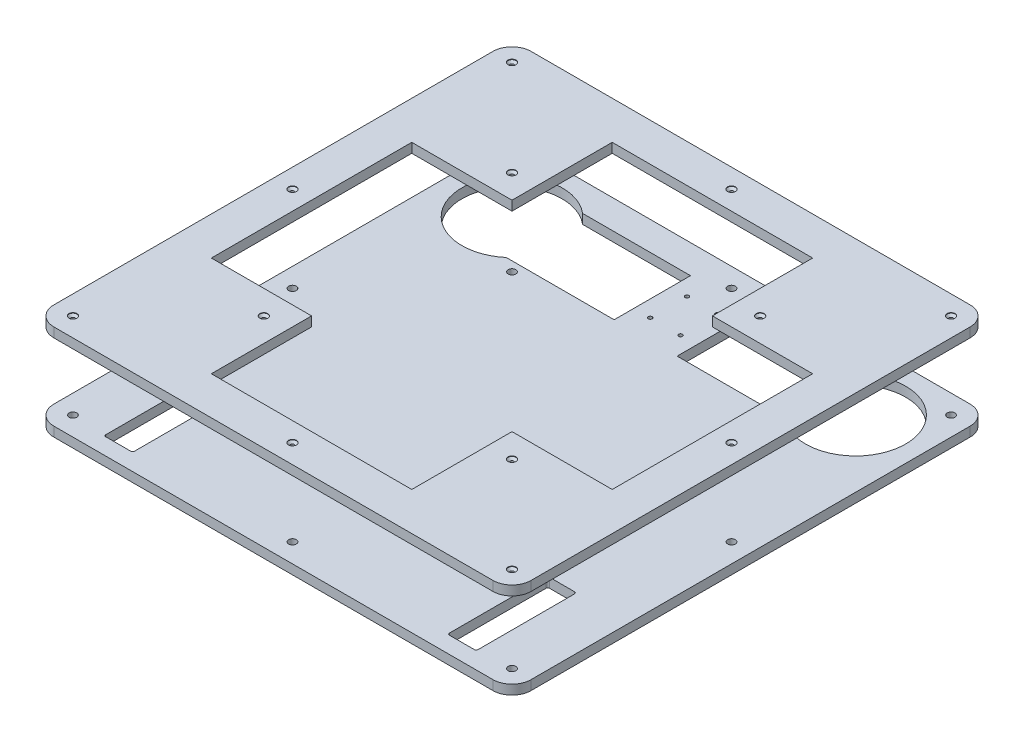
SolidWorks part; units mm, degrees
ref_plane "Front Plane" through (0, 0, 0) normal (0, 0, 1) x (1, 0, 0)
ref_plane "Top Plane" through (0, 0, 0) normal (0, 1, 0) x (1, 0, 0)
ref_plane "Right Plane" through (0, 0, 0) normal (1, 0, 0) x (0, 0, -1)
sketch "Sketch1" plane through (0, 0, 0) normal (0, 1, 0) x (1, 0, 0)
  line L0 (180, 180) -> (-180, 180) construction
  line L1 (-230, -250) -> (230, -250)
  line L2 (-250, -230) -> (-250, 230)
  line L3 (-230, 250) -> (230, 250)
  line L4 (250, -230) -> (250, 230)
  line L5 (-250, -250) -> (250, 250) construction
  line L6 (-250, 250) -> (250, -250) construction
  line L7 (0, 250) -> (0, -250) construction
  line L8 (-250, 0) -> (250, 0) construction
  line L9 (-193, -232.5) -> (-167, -232.5)
  line L10 (-195, -230.5) -> (-195, -129.5)
  line L11 (-193, -127.5) -> (-167, -127.5)
  line L12 (-165, -230.5) -> (-165, -129.5)
  line L13 (-195, -232.5) -> (-165, -127.5) construction
  line L14 (-195, -127.5) -> (-165, -232.5) construction
  line L15 (193, -232.5) -> (167, -232.5)
  line L16 (195, -230.5) -> (195, -129.5)
  line L17 (193, -127.5) -> (167, -127.5)
  line L18 (165, -230.5) -> (165, -129.5)
  line L19 (195, -232.5) -> (165, -127.5) construction
  line L20 (195, -127.5) -> (165, -232.5) construction
  line L21 (33, 220) -> (145.9963, 220)
  line L23 (33, 220) -> (33, 140)
  line L25 (-33, 220) -> (-33, 140)
  line L26 (33, 220) -> (-33, 140) construction
  line L27 (33, 140) -> (-33, 220) construction
  line L28 (33, 140) -> (145.9963, 140)
  line L29 (-33, 220) -> (-145.9963, 220)
  line L30 (-33, 140) -> (-145.9963, 140)
  arc A0 (230, 250) -> (250, 230) centre (230, 230) cw
  arc A1 (250, -230) -> (230, -250) centre (230, -230) cw
  arc A2 (-230, -250) -> (-250, -230) centre (-230, -230) cw
  arc A3 (-250, 230) -> (-230, 250) centre (-230, 230) cw
  circle A4 centre (-230, 230) radius 4
  circle A5 centre (230, 230) radius 4
  circle A6 centre (230, -230) radius 4
  circle A7 centre (-230, -230) radius 4
  arc A8 (-145.9963, 220) -> (-145.9963, 140) centre (-180, 180) ccw
  arc A9 (145.9963, 140) -> (145.9963, 220) centre (180, 180) ccw
  arc A10 (165, -230.5) -> (167, -232.5) centre (167, -230.5) ccw
  arc A11 (193, -232.5) -> (195, -230.5) centre (193, -230.5) ccw
  arc A12 (195, -129.5) -> (193, -127.5) centre (193, -129.5) ccw
  arc A13 (165, -129.5) -> (167, -127.5) centre (167, -129.5) cw
  arc A14 (-167, -127.5) -> (-165, -129.5) centre (-167, -129.5) cw
  arc A15 (-165, -230.5) -> (-167, -232.5) centre (-167, -230.5) cw
  arc A16 (-193, -232.5) -> (-195, -230.5) centre (-193, -230.5) cw
  arc A17 (-195, -129.5) -> (-193, -127.5) centre (-193, -129.5) cw
  circle A18 centre (0, 230) radius 4
  circle A19 centre (-230, 0) radius 4
  circle A20 centre (230, 0) radius 4
  circle A21 centre (0, -230) radius 4
  circle A22 centre (-130, 130) radius 4
  circle A23 centre (130, 130) radius 4
  circle A24 centre (-130, -130) radius 4
  circle A25 centre (130, -130) radius 4
  circle A27 centre (15.9096, 199.2843) radius 2
  circle A28 centre (15.9096, 160.7157) radius 2
  circle A29 centre (-15.9096, 160.7157) radius 2
  circle A30 centre (-15.9096, 199.2843) radius 2
  point P0 (0, 0)
  point P30 (-180, -180)
  point P35 (180, -180)
  point P80 (0, 180)
  point P87 (-5.6249, 208.8714)
  point P93 (0, 180)
  point P96 (0, 180)
  dimension "D3" = 20
  dimension "D4" = 8
  dimension "D5" = 105
  dimension "D10" = 2
  dimension "D11" = 2
  dimension "D7" = 66
  dimension "D14" = 4
  dimension "D1" = 500
  dimension "D2" = 500
  dimension "D6" = 30
  dimension "D8" = 80
  dimension "D9" = 70
  dimension "D12" = 50
sketch "Sketch2" plane through (0, 0, 0) normal (0, 0, 1) x (1, 0, 0)
  line L0 (0, 0) -> (0, 80) construction
  dimension "D1" = 80
ref_plane "Plane1" through (0, 80, 0) normal (0, 1, 0) x (1, 0, 0)
sketch "Sketch3" plane through (0, 80, 0) normal (0, 1, 0) x (1, 0, 0)
  line L0 (250, 0) -> (-250, 0) construction
  line L1 (-230, -250) -> (230, -250)
  line L2 (-250, -230) -> (-250, 230)
  line L3 (-230, 250) -> (230, 250)
  line L4 (250, -230) -> (250, 230)
  line L5 (-250, -250) -> (250, 250) construction
  line L6 (-250, 250) -> (250, -250) construction
  line L7 (-105, -210) -> (105, -210)
  line L8 (-105, -210) -> (-105, 210)
  line L9 (-105, 210) -> (105, 210)
  line L10 (105, -210) -> (105, 210)
  line L11 (-105, -210) -> (105, 210) construction
  line L12 (-105, 210) -> (105, -210) construction
  line L13 (-210, -105) -> (210, -105)
  line L14 (-210, -105) -> (-210, 105)
  line L15 (-210, 105) -> (210, 105)
  line L16 (210, -105) -> (210, 105)
  line L17 (-210, -105) -> (210, 105) construction
  line L18 (-210, 105) -> (210, -105) construction
  line L19 (0, 250) -> (0, -250) construction
  arc A0 (230, 250) -> (250, 230) centre (230, 230) cw
  arc A1 (250, -230) -> (230, -250) centre (230, -230) cw
  arc A2 (-230, -250) -> (-250, -230) centre (-230, -230) cw
  arc A3 (-250, 230) -> (-230, 250) centre (-230, 230) cw
  circle A4 centre (-230, 230) radius 2
  circle A6 centre (230, 230) radius 2
  circle A7 centre (230, -230) radius 2
  circle A8 centre (-230, -230) radius 2
  circle A9 centre (0, 230) radius 2
  circle A10 centre (-130, 130) radius 2
  circle A11 centre (130, 130) radius 2
  circle A12 centre (-230, 0) radius 2
  circle A13 centre (0, -230) radius 2
  circle A14 centre (230, 0) radius 2
  circle A15 centre (130, -130) radius 2
  circle A16 centre (-130, -130) radius 2
  point P0 (0, 0)
  point P19 (0, 0)
  point P24 (0, 230)
  point P25 (130, 130)
  point P27 (230, 0)
  point P29 (130, -130)
  point P31 (-130, -130)
  point P33 (-230, 0)
  point P35 (0, -230)
  point P37 (-130, 130)
  point P39 (0, 0)
  dimension "D1" = 20
  dimension "D4" = 4
  dimension "D2" = 20
  dimension "D3" = 25
extrude "Boss-Extrude1" add sketch "Sketch1" against normal blind 10
extrude "Boss-Extrude2" add sketch "Sketch3" along normal blind 10 separate body contours A3 L2 A2 L1 A1 L4 A0 L3 L16 L13 L10 L7 L8 L14 L15 L9
sketch "Sketch4" plane through (0, 90, 0) normal (0, 1, 0) x (1, 0, 0)
  circle A0 centre (-230, 230) radius 4.2
  dimension "D1" = 8.4
sketch "Sketch8" plane through (0, 90, 0) normal (0, 1, 0) x (1, 0, 0)
  circle A0 centre (-230, 230) radius 4.2
  circle A1 centre (0, 230) radius 4.2
  circle A2 centre (230, 230) radius 4.2
  circle A3 centre (-130, 130) radius 4.2
  circle A4 centre (-230, 0) radius 4.2
  circle A5 centre (-130, -130) radius 4.2
  circle A6 centre (130, 130) radius 4.2
  circle A7 centre (230, 0) radius 4.2
  circle A8 centre (130, -130) radius 4.2
  circle A9 centre (230, -230) radius 4.2
  circle A10 centre (0, -230) radius 4.2
  circle A11 centre (-230, -230) radius 4.2
  dimension "D1" = 8.4
extrude "Cut-Extrude3" cut sketch "Sketch8" against normal blind 0.5
ref_plane "Plane4" through (0, 0, -228) normal (0, 0, -1) x (-1, 0, 0)
sketch "Sketch9" plane through (0, 0, -228) normal (0, 0, -1) x (-1, 0, 0)
  line L0 (230, 90) -> (230, 80) construction
  line L1 (234.2, 90) -> (225.8, 90) construction
  point P0 (230, 87.3)
  dimension "D1" = 2.7
ref_plane "Plane5" through (0, 87.3, 0) normal (0, 1, 0) x (1, 0, 0)
sketch "Sketch10" plane through (0, 87.3, 0) normal (0, 1, 0) x (1, 0, 0)
  circle A0 centre (-230, -230) radius 2 construction
  circle A1 centre (-130, -130) radius 2 construction
  circle A2 centre (0, -230) radius 2 construction
  circle A3 centre (230, -230) radius 2 construction
  circle A4 centre (130, -130) radius 2 construction
  circle A5 centre (230, 0) radius 2 construction
  circle A6 centre (130, 130) radius 2 construction
  circle A7 centre (230, 230) radius 2 construction
  circle A8 centre (0, 230) radius 2 construction
  circle A9 centre (-130, 130) radius 2 construction
  circle A10 centre (-230, 0) radius 2 construction
  circle A11 centre (-230, 230) radius 2 construction
  circle A12 centre (-230, -230) radius 2
  circle A13 centre (-130, -130) radius 2
  circle A14 centre (0, -230) radius 2
  circle A15 centre (230, -230) radius 2
  circle A16 centre (130, -130) radius 2
  circle A17 centre (230, 0) radius 2
  circle A18 centre (130, 130) radius 2
  circle A19 centre (230, 230) radius 2
  circle A20 centre (0, 230) radius 2
  circle A21 centre (-130, 130) radius 2
  circle A22 centre (-230, 0) radius 2
  circle A23 centre (-230, 230) radius 2
extrude "Cut-Extrude4" cut sketch "Sketch10" along normal up to surface (2.2 mm away) draft 45
